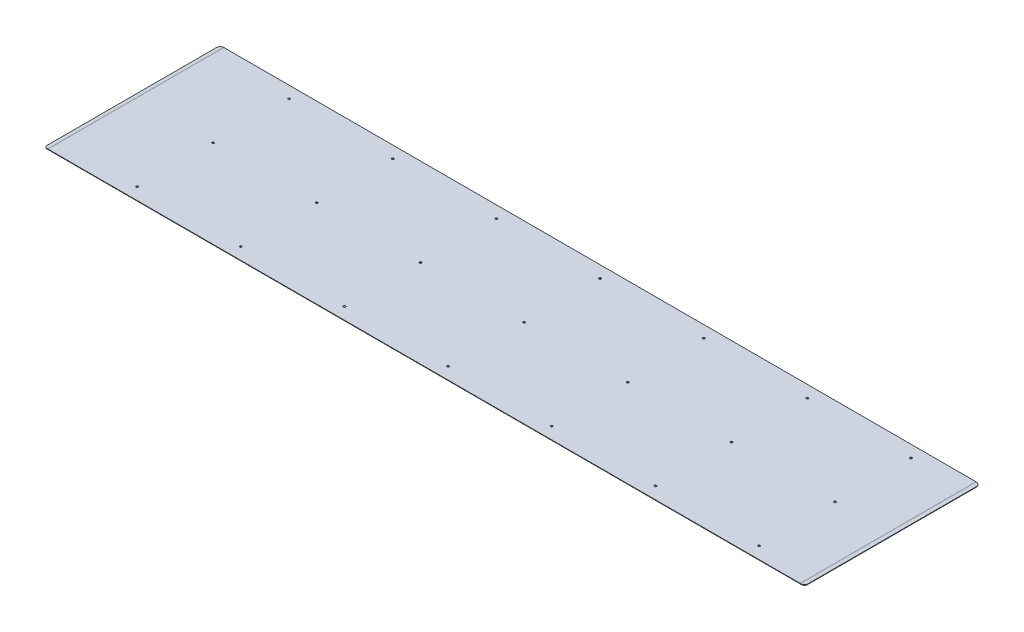
SolidWorks part; units mm, degrees
material "1.4541 (X6CrNiTi18-10)"
ref_plane "Piano frontale" through (0, 0, 0) normal (0, 0, 1) x (1, 0, 0)
ref_plane "Piano superiore" through (0, 0, 0) normal (0, 1, 0) x (1, 0, 0)
ref_plane "Piano destro" through (0, 0, 0) normal (1, 0, 0) x (0, 0, -1)
sketch "Schizzo1" plane through (0, 0, 0) normal (0, 0, 1) x (1, 0, 0)
  line L0 (-1089.2324, 0.7062) -> (-1100, -0.2358)
  line L1 (1087.0343, -0.75) -> (-1087.0343, -0.75)
  line L3 (1088.2301, 0.75) -> (-1088.2301, 0.75)
  line L5 (1100, -0.75) -> (-1100, 0.75) construction
  line L6 (1099.9539, 0.7499) -> (-1099.955, -0.7499) construction
  line L7 (-1100, -0.2358) -> (-1099.8602, -1.8339)
  line L8 (-1099.8602, -1.8339) -> (-1087.9058, -0.7881)
  line L9 (0, 127.7309) -> (0, -125.3362) construction
  line L10 (1099.8602, -1.8339) -> (1087.9058, -0.7881)
  line L11 (1100, -0.2358) -> (1099.8602, -1.8339)
  line L12 (1089.2324, 0.7062) -> (1100, -0.2358)
  arc A0 (-1087.9058, -0.7881) -> (-1087.0343, -0.75) centre (-1087.0343, -10.75) cw
  arc A1 (-1089.2324, 0.7062) -> (-1088.2301, 0.75) centre (-1088.2301, -10.75) cw
  arc A2 (1089.2324, 0.7062) -> (1088.2301, 0.75) centre (1088.2301, -10.75) ccw
  arc A3 (1087.9058, -0.7881) -> (1087.0343, -0.75) centre (1087.0343, -10.75) ccw
  point P0 (0, 0)
  dimension "D4" = 10
  dimension "D5" = 11.5
  dimension "D1" = 12
  dimension "D7" = 12
  dimension "D2" = 1.5
  dimension "D3" = 175
  dimension "D6" = 2200
extrude "Estrusione-Estrusione1" add sketch "Schizzo1" along normal mid plane 509
fillet "Raccordo1" radius 10 4 edges at (-1099.9301, -1.0349, 254.5) (-1099.9301, -1.0349, -254.5) (1099.9301, -1.0349, -254.5) (1099.9301, -1.0349, 254.5)
sketch "Schizzo2" plane through (0, 0.75, 0) normal (0, 1, 0) x (1, 0, 0)
  line L0 (35, 292.6246) -> (35, -328.2908) construction
  line L1 (-1155.0973, 0) -> (1190.7634, 0) construction
  circle A2 centre (35, -220) radius 3
  circle A3 centre (35, 220) radius 3
  circle A5 centre (35, 0) radius 3
  dimension "D1" = 6
  dimension "D5" = 6
  dimension "D6" = 6
  dimension "D2" = 35
  dimension "D3" = 440
  dimension "D4" = 220
extrude "Taglio-Estrusione1" cut sketch "Schizzo2" against normal blind 2
pattern_linear "Ripetizione a L1" count 4 spacing 300 along (1, 0, 0) count 4 spacing 300 along (-1, 0, 0) of "Taglio-Estrusione1"
